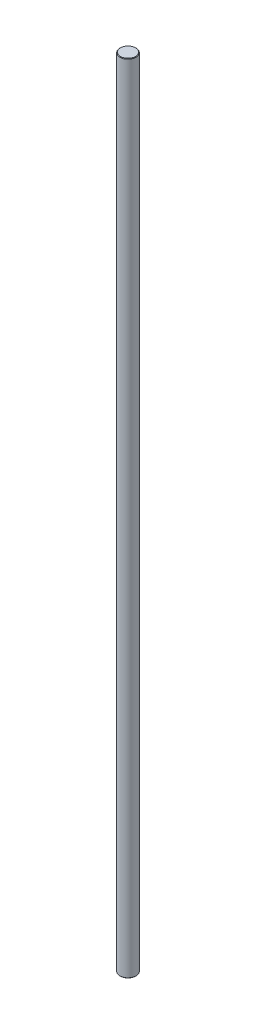
SolidWorks part; units mm, degrees
material "1.4571 (X6CrNiMoTi17-12-2)"
ref_plane "Płaszczyzna przednia" through (0, 0, 0) normal (0, 0, 1) x (1, 0, 0)
ref_plane "Płaszczyzna górna" through (0, 0, 0) normal (0, 1, 0) x (1, 0, 0)
ref_plane "Płaszczyzna prawa" through (0, 0, 0) normal (1, 0, 0) x (0, 0, -1)
sketch "Szkic1" plane through (0, 0, 0) normal (0, 1, 0) x (1, 0, 0)
  circle A0 centre (-19.4218, 6.0076) radius 4
extrude "Dodanie-wyciągnięcie1" add sketch "Szkic1" along normal blind 398
chamfer "Sfazowanie1" distance 0.25 angle 45 2 edges at (-19.4218, 398, -2.0076) (-19.4218, 0, -2.0076)
